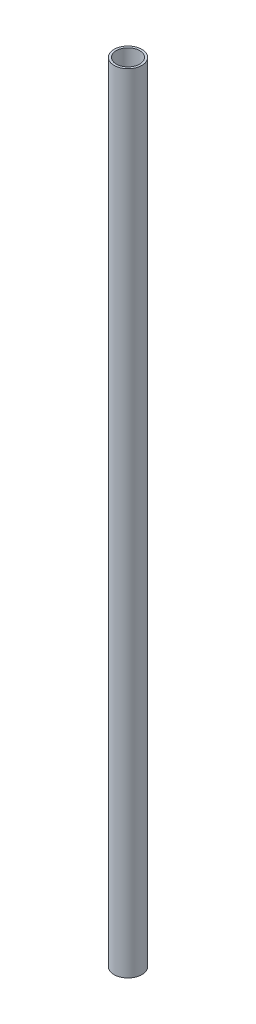
SolidWorks part; units mm, degrees
ref_plane "Front Plane" through (0, 0, 0) normal (0, 0, 1) x (1, 0, 0)
ref_plane "Top Plane" through (0, 0, 0) normal (0, 1, 0) x (1, 0, 0)
ref_plane "Right Plane" through (0, 0, 0) normal (1, 0, 0) x (0, 0, -1)
sketch "Sketch1" plane through (0, 0, 0) normal (0, 1, 0) x (1, 0, 0)
  circle A0 centre (0, 0) radius 15.905
  circle A1 centre (0, 0) radius 13.405
  dimension "D1" = 31.81
  dimension "D2" = 2.5
extrude "Boss-Extrude1" add sketch "Sketch1" against normal blind 900
